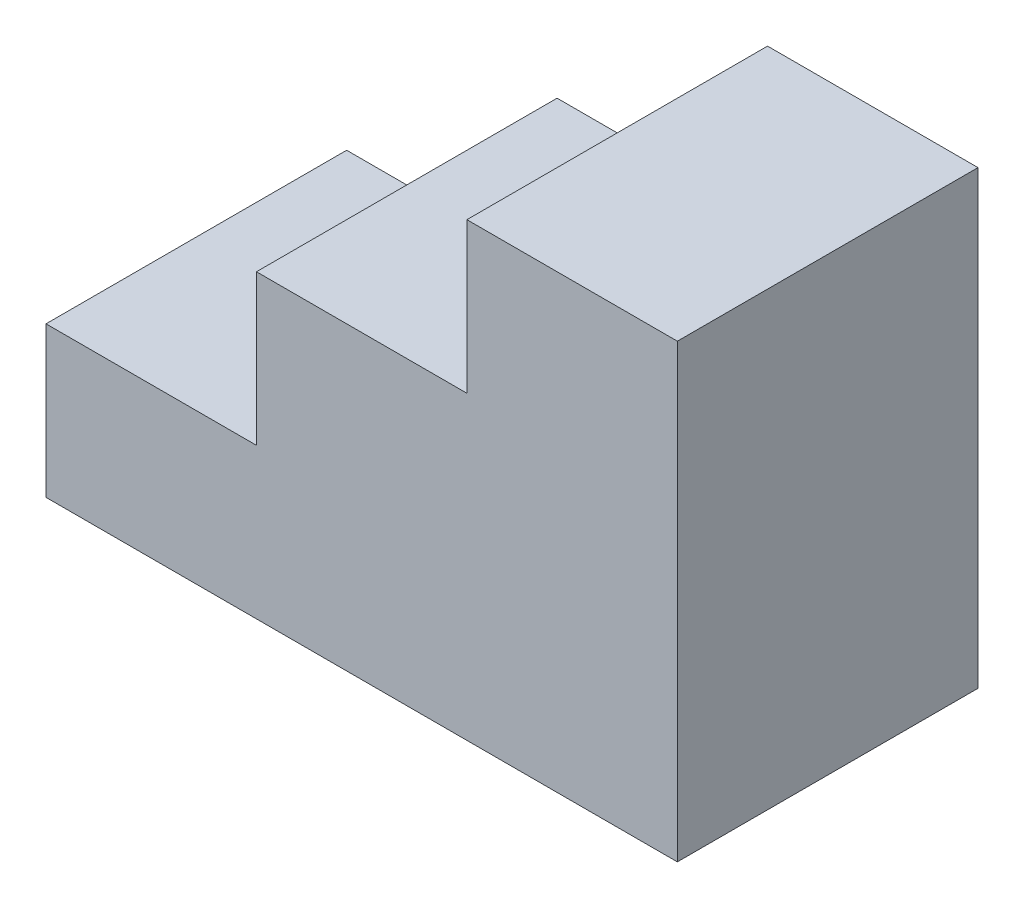
SolidWorks part; units mm, degrees
ref_plane "Front Plane" through (0, 0, 0) normal (0, 0, 1) x (1, 0, 0)
ref_plane "Top Plane" through (0, 0, 0) normal (0, 1, 0) x (1, 0, 0)
ref_plane "Right Plane" through (0, 0, 0) normal (1, 0, 0) x (0, 0, -1)
sketch "Sketch1" plane through (0, 0, 0) normal (0, 0, 1) x (1, 0, 0)
  line L0 (0, 0) -> (105, 0)
  line L1 (105, 0) -> (105, 75)
  line L2 (105, 75) -> (70, 75)
  line L3 (70, 75) -> (70, 50)
  line L4 (70, 50) -> (35, 50)
  line L5 (35, 50) -> (35, 25)
  line L6 (35, 25) -> (0, 25)
  line L7 (0, 25) -> (0, 0)
  dimension "D1" = 105
  dimension "D2" = 75
  dimension "D3" = 35
  dimension "D4" = 35
  dimension "D5" = 25
  dimension "D6" = 25
extrude "Boss-Extrude1" add sketch "Sketch1" along normal blind 50 contours L7 L0 L1 L2 L3 L4 L5 L6
